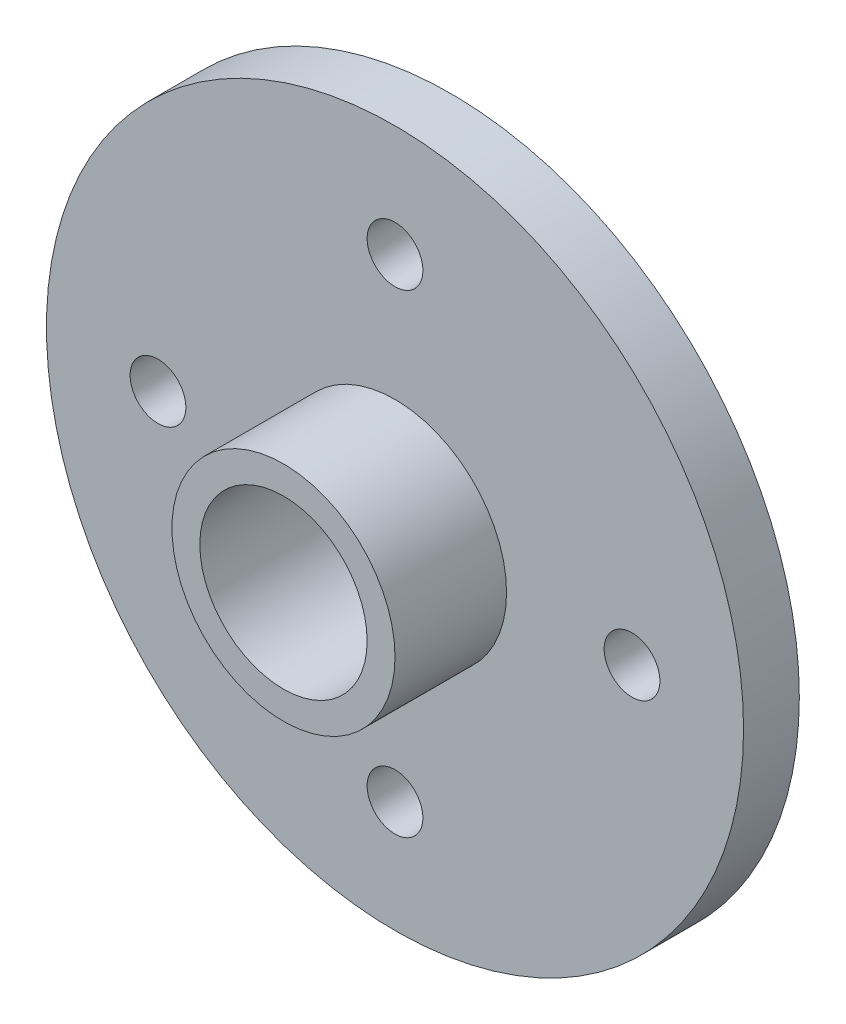
SolidWorks part; units mm, degrees
ref_plane "Front Plane" through (0, 0, 0) normal (0, 0, 1) x (1, 0, 0)
ref_plane "Top Plane" through (0, 0, 0) normal (0, 1, 0) x (1, 0, 0)
ref_plane "Right Plane" through (0, 0, 0) normal (1, 0, 0) x (0, 0, -1)
sketch "Sketch1" plane through (0, 0, 0) normal (0, 0, 1) x (1, 0, 0)
  circle A0 centre (0, 0) radius 12.5
  circle A1 centre (0, 0) radius 8.5 construction
  circle A2 centre (-8.5, 0) radius 1
  circle A3 centre (0, 8.5) radius 1
  circle A4 centre (8.5, 0) radius 1
  circle A5 centre (0, -8.5) radius 1
  point P15 (0, 0)
  dimension "D1" = 25
  dimension "D2" = 2
  dimension "D3" = 17
  dimension "D4" = 4
extrude "Boss-Extrude1" add sketch "Sketch1" along normal blind 2
sketch "Sketch2" plane through (0, 0, 2) normal (0, 0, 1) x (1, 0, 0)
  circle A0 centre (0, 0) radius 3
  circle A1 centre (0, 0) radius 4
  dimension "D1" = 6
  dimension "D2" = 8
extrude "Boss-Extrude2" add sketch "Sketch2" along normal blind 4
sketch "Sketch3" plane through (0, 0, 0) normal (0, 0, -1) x (-1, 0, 0)
  circle A0 centre (0, 0) radius 3
  dimension "D1" = 6
extrude "Cut-Extrude1" cut sketch "Sketch3" against normal through all
